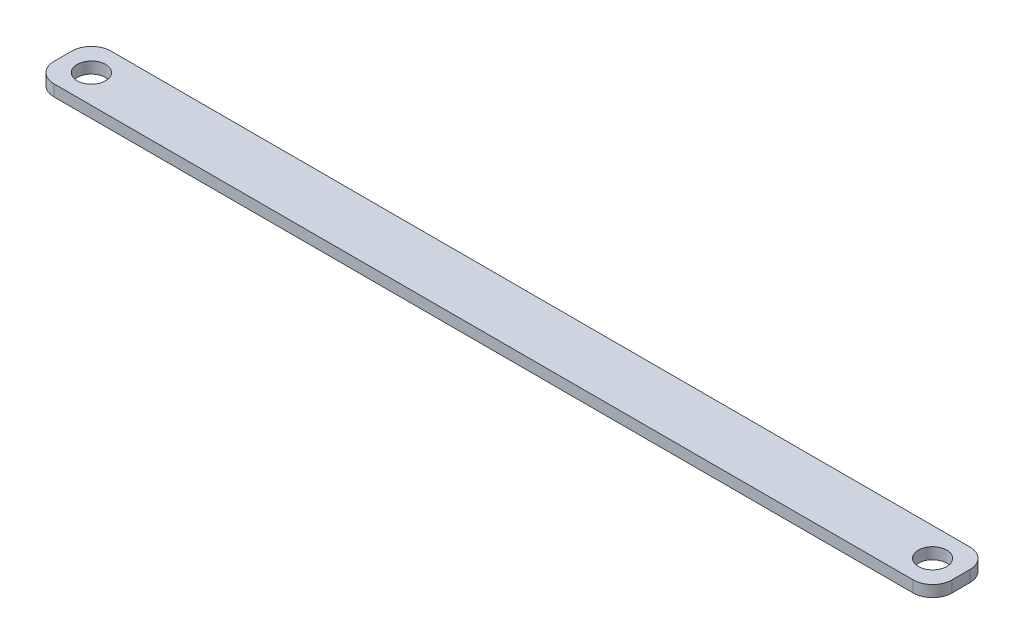
SolidWorks part; units mm, degrees
ref_plane "Front Plane" through (0, 0, 0) normal (0, 0, 1) x (1, 0, 0)
ref_plane "Top Plane" through (0, 0, 0) normal (0, 1, 0) x (1, 0, 0)
ref_plane "Right Plane" through (0, 0, 0) normal (1, 0, 0) x (0, 0, -1)
sketch "Sketch1" plane through (0, 0, 0) normal (0, 1, 0) x (1, 0, 0)
  line L1 (-17.1113, 0) -> (-772.8887, 0)
  line L2 (0, -17.1113) -> (0, -32.8887)
  line L3 (-17.1113, -50) -> (-772.8887, -50)
  line L4 (-790, -17.1113) -> (-790, -32.8887)
  circle A0 centre (-765, -25) radius 12.5
  circle A1 centre (-25, -25) radius 12.5
  arc A2 (0, -32.8887) -> (-17.1113, -50) centre (-17.1113, -32.8887) cw
  arc A3 (-17.1113, 0) -> (0, -17.1113) centre (-17.1113, -17.1113) cw
  arc A4 (-772.8887, -50) -> (-790, -32.8887) centre (-772.8887, -32.8887) cw
  arc A5 (-772.8887, 0) -> (-790, -17.1113) centre (-772.8887, -17.1113) ccw
  point P11 (-1174.846, 88.3149)
  point P12 (0, -50)
  point P15 (0, 0)
  point P20 (-790, 0)
  dimension "D3" = 25
  dimension "D6" = 25
  dimension "D9" = 17.1113
  dimension "D1" = 790
  dimension "D2" = 50
  dimension "D4" = 25
  dimension "D5" = 25
  dimension "D7" = 25
  dimension "D8" = 25
extrude "Boss-Extrude1" add sketch "Sketch1" along normal blind 10
equation "\"D6@Sketch1\"=\"D3@Sketch1\""
equation "\"D7@Sketch1\"=\"D4@Sketch1\""
equation "\"D8@Sketch1\"=\"D5@Sketch1\""
